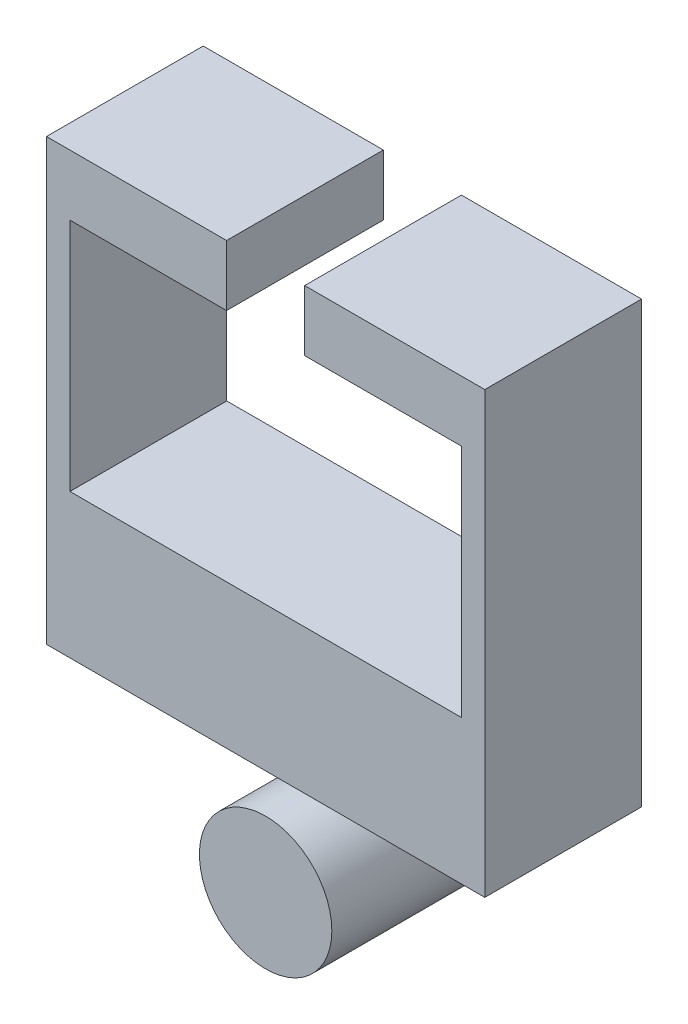
SolidWorks part; units mm, degrees
material "6061-T6 (SS)"
ref_plane "Front Plane" through (0, 0, 0) normal (0, 0, 1) x (1, 0, 0)
ref_plane "Top Plane" through (0, 0, 0) normal (0, 1, 0) x (1, 0, 0)
ref_plane "Right Plane" through (0, 0, 0) normal (1, 0, 0) x (0, 0, -1)
sketch "Sketch1" plane through (0, 0, 0) normal (0, 0, 1) x (1, 0, 0)
  line L0 (-35.5117, 17.0688) -> (35.5117, 17.0688)
  line L1 (35.5117, 17.0688) -> (35.5117, 88.3368)
  line L2 (35.5117, 88.3368) -> (6.3246, 88.3368)
  line L3 (6.3246, 88.3368) -> (6.3246, 78.5033)
  line L4 (6.3246, 78.5033) -> (31.7043, 78.5033)
  line L5 (31.7043, 78.5033) -> (31.7043, 40.4287)
  line L6 (31.7043, 40.4287) -> (-31.7043, 40.4287)
  line L7 (-31.7043, 40.4287) -> (-31.7043, 78.5033)
  line L8 (-31.7043, 78.5033) -> (-6.3246, 78.5033)
  line L9 (-6.3246, 78.5033) -> (-6.3246, 88.3368)
  line L10 (-6.3246, 88.3368) -> (-35.5117, 88.3368)
  line L11 (-35.5117, 88.3368) -> (-35.5117, 17.0688)
  line L12 (0, 0) -> (0, 17.0688) construction
  circle A0 centre (0, 0) radius 10.7287
  dimension "D1" = 21.4574
  dimension "D5" = 38.0746
  dimension "D6" = 71.0235
  dimension "D7" = 3.8075
  dimension "D8" = 9.8334
  dimension "D11" = 23.3599
  dimension "D12" = 17.0688
  dimension "D2" = 63.4086
  dimension "D3" = 29.1871
extrude "Boss-Extrude1" add sketch "Sketch1" along normal blind 25.4
sketch "Sketch2" plane through (0, 17.0688, 0) normal (0, -1, 0) x (1, 0, 0)
  line L0 (-10.7287, 25.4) -> (-10.7287, 0) construction
  line L1 (-10.7287, 0) -> (10.7287, 0)
  line L2 (-10.7287, 0) -> (-10.7287, 4.041)
  line L3 (-10.7287, 4.041) -> (10.7287, 4.041)
  line L4 (10.7287, 0) -> (10.7287, 4.041)
  line L5 (10.7287, 0) -> (10.7287, 25.4) construction
  line L6 (-10.7287, 0) -> (10.7287, 0) construction
  dimension "D1" = 4.041
extrude "Boss-Extrude2" add sketch "Sketch2" along normal blind 17.0688
equation "\"SF\"= 4"
equation "\"YieldS\"= 40000"
equation "\"E\"= 10 ^ 6"
equation "\"b\"= 1"
equation "\"F\"= 500"
equation "\"La\"= 1"
equation "\"Za\"= \"F\" * \"SF\" * \"La\" * 2 / ( \"YieldS\" * 2 )"
equation "\"Defl\"= 0.005"
equation "\"Da\"= ( ( 16 * \"F\" * \"La\" ) / ( \"E\" * \"Defl\" * pi ) ) ^ ( 1 / 4 )"
equation "\"Lb\"= .672"
equation "\"bb\"= \"Da\""
equation "\"hb\"= ( 2 * \"F\" * \"Lb\" ) / ( \"bb\" * \"E\" * \"Defl\" )"
equation "\"Lc\"= 2.4964"
equation "\"hc\"= ( ( 24 * \"F\" * ( \"Lc\" ^ 3 ) ) / ( 48 * \"E\" * \"b\" * \"Defl\" ) ) ^ ( 1 / 3 )"
equation "\"Ld\"= 1.499"
equation "\"hd\"= ( \"F\" * \"Ld\" ) / ( \"E\" * \"b\" * \"Defl\" )"
equation "\"Le\"= 0.9992"
equation "\"he\"= ( ( \"SF\" * \"F\" * \"Le\" * 3 ) / ( \"YieldS\" * \"b\" ) ) ^ ( 1 / 2 )"
equation "\"D1@Sketch1\"=\"Da\""
equation "\"D12@Sketch1\"=\"Lb\""
equation "\"D11@Sketch1\"=\"hc\""
equation "\"D5@Sketch1\"=\"Ld\""
equation "\"D8@Sketch1\"=\"he\""
equation "\"D7@Sketch1\"=\"hd\""
equation "\"D1@Sketch2\"=\"hb\""
equation "\"D2@Sketch1\"=\"Lc\""
equation "\"bottomL\"= \"Lc\" + 2 * \"hd\""
equation "\"D6@Sketch1\"=\"bottomL\""
